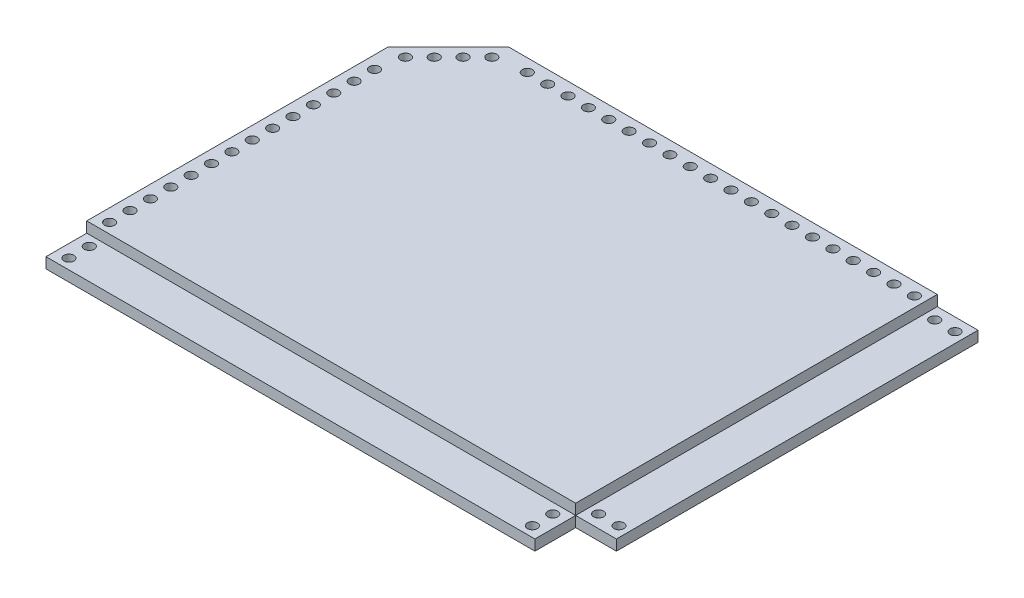
SolidWorks part; units mm, degrees
ref_plane "Front Plane" through (0, 0, 0) normal (0, 0, 1) x (1, 0, 0)
ref_plane "Top Plane" through (0, 0, 0) normal (0, 1, 0) x (1, 0, 0)
ref_plane "Right Plane" through (0, 0, 0) normal (1, 0, 0) x (0, 0, -1)
sketch "Sketch2" plane through (0, 0, 0) normal (0, 1, 0) x (1, 0, 0)
  line L0 (-73.1672, 26.9845) -> (-55.2067, 44.945)
  line L1 (-73.1672, 44.945) -> (85.3288, 44.945)
  line L2 (-73.1672, 44.945) -> (-73.1672, -75.451)
  line L3 (-73.1672, -75.451) -> (85.3288, -75.451)
  line L4 (85.3288, 44.945) -> (85.3288, -75.451)
  dimension "D1" = 158.496
  dimension "D2" = 120.396
  dimension "D3" = 25.4
  dimension "D4" = 45
extrude "Boss-Extrude1" add sketch "Sketch2" along normal blind 6.35 contours L4 L1 L0 L2 L3
sketch "Sketch3" plane through (0, 6.35, 0) normal (0, 1, 0) x (1, 0, 0)
  line L0 (-55.2067, 44.945) -> (85.3288, 44.945) construction
  line L1 (85.3288, 44.945) -> (85.3288, -75.451) construction
  circle A0 centre (82.2808, 41.135) radius 1.5
  dimension "D3" = 3
  dimension "D1" = 3.81
  dimension "D2" = 3.048
extrude "Cut-Extrude1" cut sketch "Sketch3" against normal blind 6.35 contours A0
pattern_linear "LPattern2" count 22 spacing 6.096 along (-1, 0, 0) of "Cut-Extrude1"
sketch "Sketch4" plane through (0, 6.35, 0) normal (0, 1, 0) x (1, 0, 0)
  line L0 (-73.1672, 26.9845) -> (-73.1672, -75.451) construction
  line L1 (-73.1672, -75.451) -> (85.3288, -75.451) construction
  circle A0 centre (-69.3572, -72.403) radius 1.5
  dimension "D1" = 3
  dimension "D2" = 3.81
  dimension "D3" = 3.048
extrude "Cut-Extrude2" cut sketch "Sketch4" against normal blind 6.35
pattern_linear "LPattern3" count 16 spacing 6.096 along (0, 0, -1) of "Cut-Extrude2"
sketch "Sketch6" plane through (85.3288, 0, 0) normal (1, 0, 0) x (0, 0, -1)
  line L0 (44.945, 6.35) -> (-75.451, 6.35) construction
  line L1 (-75.451, 6.35) -> (44.945, 6.35)
  line L2 (-75.451, 6.35) -> (-75.451, 3.175)
  line L3 (-75.451, 3.175) -> (44.945, 3.175)
  line L4 (44.945, 6.35) -> (44.945, 3.175)
  line L5 (-75.451, 6.35) -> (-75.451, 0) construction
  line L6 (44.945, 6.35) -> (44.945, 0) construction
  dimension "D1" = 3.175
  dimension "D2" = 0
  dimension "D3" = 0
  dimension "D4" = 0
extrude "Cut-Extrude3" cut sketch "Sketch6" against normal blind 12.192
sketch "Sketch7" plane through (0, 0, 75.451) normal (0, 0, 1) x (1, 0, 0)
  line L1 (73.1368, 3.175) -> (-73.1672, 3.175)
  line L2 (73.1368, 3.175) -> (73.1368, 6.35)
  line L3 (73.1368, 6.35) -> (-73.1672, 6.35)
  line L4 (-73.1672, 3.175) -> (-73.1672, 6.35)
extrude "Cut-Extrude4" cut sketch "Sketch7" against normal blind 12.192
sketch "Sketch8" plane through (0, 3.175, 0) normal (0, 1, 0) x (1, 0, 0)
  line L1 (85.3288, -75.451) -> (73.1368, -75.451)
  line L2 (85.3288, -75.451) -> (85.3288, -63.259)
  line L3 (85.3288, -63.259) -> (73.1368, -63.259)
  line L4 (73.1368, -75.451) -> (73.1368, -63.259)
  dimension "D1" = 12.192
  dimension "D2" = 12.192
extrude "Cut-Extrude5" cut sketch "Sketch8" against normal blind 6.35
sketch "Sketch9" plane through (0, 3.175, 0) normal (0, 1, 0) x (1, 0, 0)
  line L0 (85.3288, -63.259) -> (73.1368, -63.259) construction
  line L1 (73.1368, -63.259) -> (73.1368, -75.451) construction
  line L2 (73.1368, -63.259) -> (-73.1672, -63.259) construction
  line L3 (-73.1672, -75.451) -> (73.1368, -75.451) construction
  line L4 (73.1368, 44.945) -> (73.1368, -63.259) construction
  line L5 (85.3288, -63.259) -> (85.3288, 44.945) construction
  circle A0 centre (69.3268, -66.307) radius 1.5
  circle A1 centre (69.3268, -72.403) radius 1.5
  circle A2 centre (76.1848, -59.449) radius 1.5
  circle A3 centre (82.2808, -59.449) radius 1.5
  dimension "D1" = 3
  dimension "D2" = 3
  dimension "D3" = 3
  dimension "D4" = 3
  dimension "D9" = 3.048
  dimension "D5" = 3.81
  dimension "D6" = 3.81
  dimension "D7" = 3.81
  dimension "D8" = 3.81
  dimension "D10" = 3.048
  dimension "D11" = 3.048
  dimension "D12" = 3.048
extrude "Cut-Extrude6" cut sketch "Sketch9" against normal blind 6.35
sketch "Sketch10" plane through (0, 6.35, 0) normal (0, 1, 0) x (1, 0, 0)
  line L0 (-73.1672, 26.9845) -> (-54.9179, 26.9845)
  line L1 (-54.9179, 26.9845) -> (-55.2067, 44.945)
  line L2 (-55.2067, 44.945) -> (-73.1672, 26.9845)
  line L3 (-64.1869, 35.9647) -> (-54.9179, 26.9845)
  circle A0 centre (-59.2947, 35.4688) radius 1.5
  circle A1 centre (-63.6058, 31.1578) radius 1.5
  circle A2 centre (-54.9842, 39.7794) radius 1.5
  circle A3 centre (-67.9163, 26.8473) radius 1.5
  dimension "D1" = 3
  dimension "D2" = 3
  dimension "D8" = 3
  dimension "D9" = 3
  dimension "D3" = 3.048
  dimension "D4" = 3.048
  dimension "D5" = 3.81
  dimension "D6" = 3.81
  dimension "D7" = 3.81
  dimension "D10" = 6.096
  dimension "D11" = 6.096
  dimension "D12" = 3.81
extrude "Cut-Extrude7" cut sketch "Sketch10" against normal blind 6.35 contours A2 | A0 | A1 | A3
